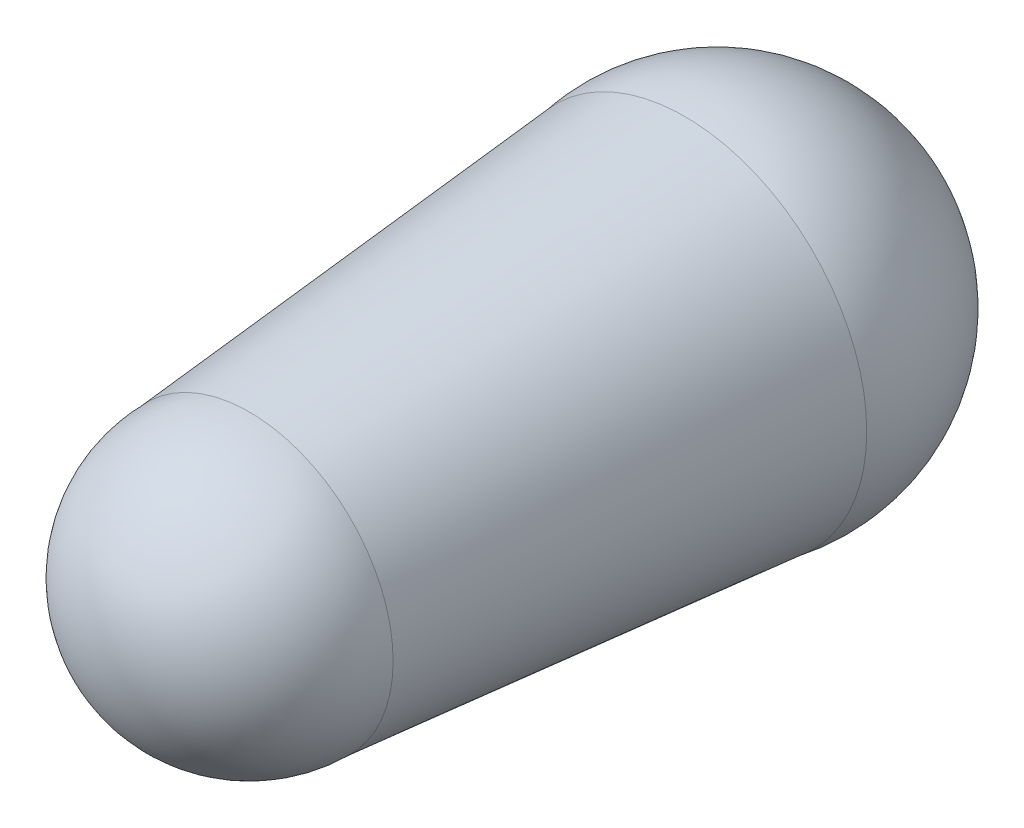
SolidWorks part; units mm, degrees
ref_plane "Front Plane" through (0, 0, 0) normal (0, 0, 1) x (1, 0, 0)
ref_plane "Top Plane" through (0, 0, 0) normal (0, 1, 0) x (1, 0, 0)
ref_plane "Right Plane" through (0, 0, 0) normal (1, 0, 0) x (0, 0, -1)
sketch "Sketch1" plane through (0, 0, 0) normal (0, 0, 1) x (1, 0, 0)
  line L0 (0, 3.95) -> (0, -3.95) construction
  line L1 (0, 3.95) -> (0, -3.95)
  arc A0 (0, -3.95) -> (0, 3.95) centre (0, 0) ccw
  dimension "D1" = 7.9
revolve "Revolve1" add sketch "Sketch1" angle 360 about L0
sketch "Sketch2" plane through (0, 0, 0) normal (0, 0, 1) x (1, 0, 0)
  circle A0 centre (0, 0) radius 3.95
extrude "Boss-Extrude1" add sketch "Sketch2" along normal blind 10 draft 5
sketch "Sketch3" plane through (0, 0, 10) normal (0, 0, 1) x (1, 0, 0)
  line L0 (0, 3.0751) -> (0, -3.0751) construction
  line L1 (0, 3.0751) -> (0, -3.0751)
  arc A0 (0, -3.0751) -> (0, 3.0751) centre (0, 0) ccw
revolve "Revolve2" add sketch "Sketch3" angle 360 about L0
